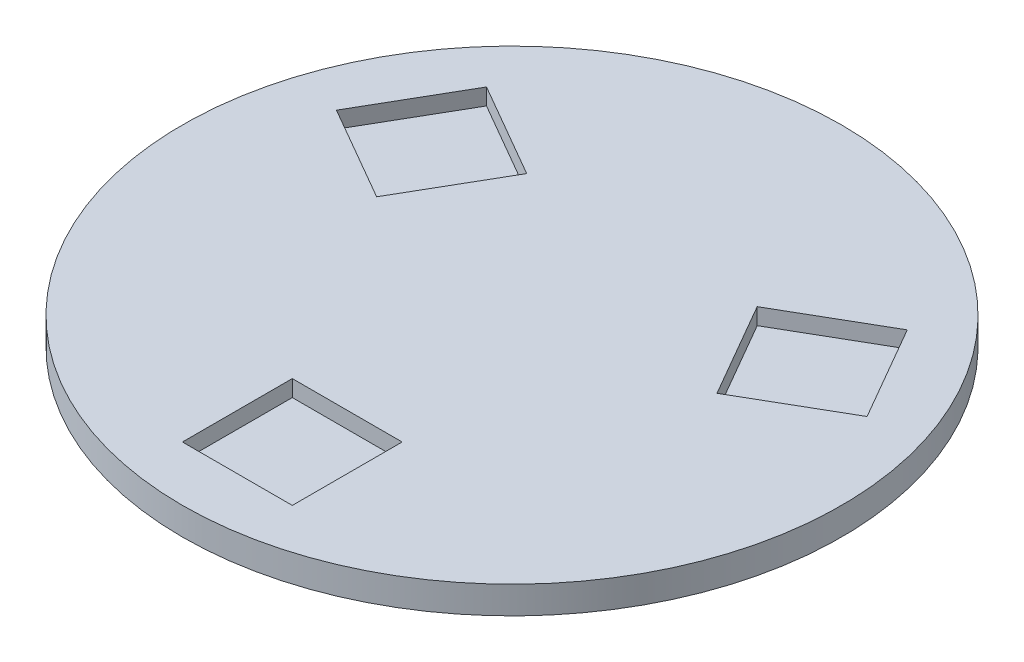
SolidWorks part; units mm, degrees
material "1060 Alloy"
ref_plane "Front" through (0, 0, 0) normal (0, 0, 1) x (1, 0, 0)
ref_plane "Top" through (0, 0, 0) normal (0, 1, 0) x (1, 0, 0)
ref_plane "Right" through (0, 0, 0) normal (1, 0, 0) x (0, 0, -1)
sketch "Sketch1" plane through (0, 0, 0) normal (0, 1, 0) x (1, 0, 0)
  circle A0 centre (0, 0) radius 3000
extrude "Boss-Extrude1" add sketch "Sketch1" along normal blind 250
sketch "Sketch2" plane through (0, 250, 0) normal (0, 1, 0) x (1, 0, 0)
  line L0 (0, 0) -> (0, -2000) construction
  line L2 (500, -1500) -> (-500, -1500)
  line L3 (500, -1500) -> (500, -2500)
  line L4 (500, -2500) -> (-500, -2500)
  line L5 (-500, -1500) -> (-500, -2500)
  line L6 (500, -1500) -> (-500, -2500) construction
  line L7 (500, -2500) -> (-500, -1500) construction
  dimension "D1" = 2000
  dimension "D2" = 1000
  dimension "D3" = 1000
extrude "Cut-Extrude1" cut sketch "Sketch2" against normal blind 150
pattern_circular "CirPattern1" count 3 over 360 about axis through (0, 0, 0) along (0, 1, 0) of "Cut-Extrude1"
